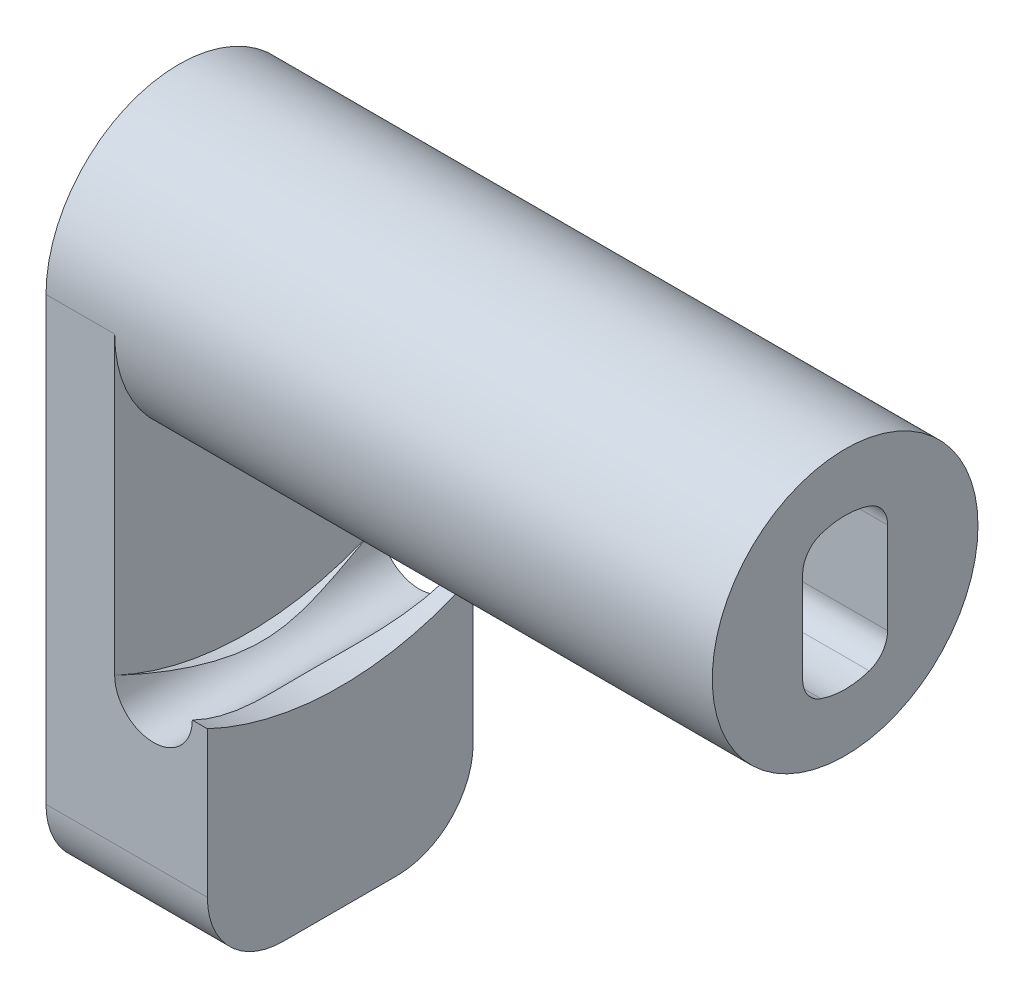
SolidWorks part; units mm, degrees
material "ABS"
ref_plane "Front Plane" through (0, 0, 0) normal (1, 0, 0) x (0, 1, 0)
ref_plane "Top Plane" through (0, 0, 0) normal (0, 0, 1) x (0, 1, 0)
ref_plane "Right Plane" through (0, 0, 0) normal (0, 1, 0) x (-1, 0, 0)
sketch "Sketch1" plane through (0, 0, 0) normal (1, 0, 0) x (0, 1, 0)
  circle A2 centre (0, 0) radius 8.7376
  dimension "D3" = 17.4752
extrude "Boss-Extrude1" add sketch "Sketch1" along normal blind 43.815
sketch "Sketch10" plane through (0, 0, 0) normal (-1, 0, 0) x (0, -1, 0)
  line L0 (0, 8.7376) -> (34.036, 8.7376)
  line L2 (34.036, 8.7376) -> (34.036, -8.7376)
  line L3 (34.036, -8.7376) -> (0, -8.7376)
  circle A0 centre (0, 0) radius 8.7376 construction
  arc A2 (0, 8.7376) -> (0, -8.7376) centre (0, 0) cw
  dimension "D1" = 34.036
extrude "Boss-Extrude3" add sketch "Sketch10" against normal blind 4.516 contours L0 A2 L3 L2
fillet "Fillet2" radius 5 2 edges at (2.258, -34.036, 8.7376) (2.258, -34.036, -8.7376)
sketch "Sketch14" [suppressed] plane through (0, 0, 0) normal (-1, 0, 0) x (0, 0, 1)
  line L0 (0.5115, -3.4237) -> (0.3944, -4.0089)
  line L1 (0, 0) -> (0, -4.064) construction
  line L2 (0, 0) -> (0.5606, -3.4335) construction
  line L3 (0.6039, -3.4087) -> (0.9011, -3.9262)
  line L4 (-0.6903, -3.3922) -> (-1.0005, -3.9021)
  line L5 (-0.5983, -3.4096) -> (-0.4961, -3.9976)
  line L6 (-1.8089, -2.9515) -> (-2.2748, -3.3245)
  line L7 (-1.7284, -2.9994) -> (-1.8334, -3.5869)
  line L8 (-2.7093, -2.1549) -> (-3.2746, -2.346)
  line L9 (-2.65, -2.2273) -> (-2.9496, -2.7435)
  line L10 (-3.2829, -1.0983) -> (-3.8795, -1.0846)
  line L11 (-3.252, -1.1867) -> (-3.7101, -1.5692)
  line L12 (-3.4605, 0.0907) -> (-4.0165, 0.3077)
  line L13 (-3.4617, -0.0029) -> (-4.023, -0.2057)
  line L14 (-3.2208, 1.2689) -> (-3.669, 1.6629)
  line L15 (-3.2539, 1.1813) -> (-3.8507, 1.1827)
  line L16 (-2.5926, 2.2939) -> (-2.879, 2.8175)
  line L17 (-2.6537, 2.223) -> (-3.214, 2.4284)
  line L18 (-1.6517, 3.0423) -> (-1.7417, 3.6323)
  line L19 (-1.7333, 2.9965) -> (-2.1896, 3.3812)
  line L20 (-0.5115, 3.4237) -> (-0.3944, 4.0089)
  line L21 (-0.6039, 3.4087) -> (-0.9011, 3.9262)
  line L22 (0.6903, 3.3922) -> (1.0005, 3.9021)
  line L23 (0.5983, 3.4096) -> (0.4961, 3.9976)
  line L24 (1.8089, 2.9515) -> (2.2748, 3.3245)
  line L25 (1.7284, 2.9994) -> (1.8334, 3.5869)
  line L26 (2.7093, 2.1549) -> (3.2746, 2.346)
  line L27 (2.65, 2.2273) -> (2.9496, 2.7435)
  line L28 (3.2829, 1.0983) -> (3.8795, 1.0846)
  line L29 (3.252, 1.1867) -> (3.7101, 1.5692)
  line L30 (3.4605, -0.0907) -> (4.0165, -0.3077)
  line L31 (3.4617, 0.0029) -> (4.023, 0.2057)
  line L32 (3.2208, -1.2689) -> (3.669, -1.6629)
  line L33 (3.2539, -1.1813) -> (3.8507, -1.1827)
  line L34 (2.5926, -2.2939) -> (2.879, -2.8175)
  line L35 (2.6537, -2.223) -> (3.214, -2.4284)
  line L36 (1.6517, -3.0423) -> (1.7417, -3.6323)
  line L37 (1.7333, -2.9965) -> (2.1896, -3.3812)
  line L38 (-0.1032, -4.0627) -> (0, -4.064)
  line L39 (-1.4865, -3.7824) -> (-1.39, -3.8189)
  line L40 (-2.6905, -3.0459) -> (-2.6123, -3.1132)
  line L41 (-3.5195, -2.032) -> (-3.57, -1.942)
  line L42 (-4.0023, -0.7057) -> (-4.0189, -0.6039)
  line L43 (-4.0023, 0.7057) -> (-3.9831, 0.8071)
  line L44 (-3.5195, 2.032) -> (-3.4668, 2.1207)
  line L45 (-2.6123, 3.1132) -> (-2.5324, 3.1785)
  line L46 (-1.39, 3.8189) -> (-1.2926, 3.853)
  line L47 (0, 4.064) -> (0.1032, 4.0627)
  line L48 (1.39, 3.8189) -> (1.4865, 3.7824)
  line L49 (2.6123, 3.1132) -> (2.6905, 3.0459)
  line L50 (3.5195, 2.032) -> (3.57, 1.942)
  line L51 (4.0023, 0.7057) -> (4.0189, 0.6039)
  line L52 (4.0023, -0.7057) -> (3.9831, -0.8071)
  line L53 (3.5195, -2.032) -> (3.4668, -2.1207)
  line L54 (2.6123, -3.1132) -> (2.5324, -3.1785)
  line L55 (1.39, -3.8189) -> (1.2926, -3.853)
  arc A0 (0.3497, -4.0489) -> (0, -4.064) centre (0, 0) cw
  arc A1 (0.3497, -4.0489) -> (0.3944, -4.0089) centre (0.3454, -3.9991) ccw
  arc A2 (0.5115, -3.4237) -> (0.6039, -3.4087) centre (0.5606, -3.4335) cw
  arc A3 (0.4203, -4.0631) -> (0.3944, -4.0089) centre (0.4434, -4.0187) cw
  arc A4 (0.4203, -4.0631) -> (0.7372, -4.2116) centre (2.3016, -0.4608) ccw
  arc A6 (0.9562, -3.9499) -> (0.9011, -3.9262) centre (0.9445, -3.9013) cw
  arc A7 (0.9562, -3.9499) -> (1.2926, -3.853) centre (0, 0) ccw
  arc A8 (-1.0562, -3.9243) -> (-1.39, -3.8189) centre (0, 0) cw
  arc A9 (-1.0562, -3.9243) -> (-1.0005, -3.9021) centre (-1.0432, -3.8761) ccw
  arc A10 (-0.6903, -3.3922) -> (-0.5983, -3.4096) centre (-0.6476, -3.4182) cw
  arc A11 (-0.4524, -4.0387) -> (-0.4961, -3.9976) centre (-0.4468, -3.9891) cw
  arc A12 (-0.4524, -4.0387) -> (-0.1032, -4.0627) centre (0, 0) ccw
  arc A13 (-2.3347, -3.3264) -> (-2.6123, -3.1132) centre (0, 0) cw
  arc A14 (-2.3347, -3.3264) -> (-2.2748, -3.3245) centre (-2.306, -3.2855) ccw
  arc A15 (-1.8089, -2.9515) -> (-1.7284, -2.9994) centre (-1.7776, -2.9906) cw
  arc A16 (-1.8064, -3.6405) -> (-1.8334, -3.5869) centre (-1.7842, -3.5957) cw
  arc A17 (-1.8064, -3.6405) -> (-1.4865, -3.7824) centre (0, 0) ccw
  arc A18 (-3.3316, -2.3273) -> (-3.5195, -2.032) centre (0, 0) cw
  arc A19 (-3.3316, -2.3273) -> (-3.2746, -2.346) centre (-3.2906, -2.2987) ccw
  arc A20 (-2.7093, -2.1549) -> (-2.65, -2.2273) centre (-2.6933, -2.2022) cw
  arc A21 (-2.9426, -2.8031) -> (-2.9496, -2.7435) centre (-2.9064, -2.7686) cw
  arc A22 (-2.9426, -2.8031) -> (-2.6905, -3.0459) centre (0, 0) ccw
  arc A23 (-3.9267, -1.0475) -> (-4.0023, -0.7057) centre (0, 0) cw
  arc A24 (-3.9267, -1.0475) -> (-3.8795, -1.0846) centre (-3.8784, -1.0346) ccw
  arc A25 (-3.2829, -1.0983) -> (-3.252, -1.1867) centre (-3.284, -1.1483) cw
  arc A26 (-3.7238, -1.6276) -> (-3.7101, -1.5692) centre (-3.678, -1.6076) cw
  arc A27 (-3.7238, -1.6276) -> (-3.57, -1.942) centre (0, 0) ccw
  arc A28 (-4.0481, 0.3587) -> (-4.0023, 0.7057) centre (0, 0) cw
  arc A29 (-4.0481, 0.3587) -> (-4.0165, 0.3077) centre (-3.9983, 0.3543) ccw
  arc A30 (-3.4605, 0.0907) -> (-3.4617, -0.0029) centre (-3.4787, 0.0442) cw
  arc A31 (-4.0559, -0.2558) -> (-4.023, -0.2057) centre (-4.006, -0.2527) cw
  arc A32 (-4.0559, -0.2558) -> (-4.0189, -0.6039) centre (0, 0) ccw
  arc A33 (-3.6813, 1.7216) -> (-3.5195, 2.032) centre (0, 0) cw
  arc A34 (-3.6813, 1.7216) -> (-3.669, 1.6629) centre (-3.636, 1.7005) ccw
  arc A35 (-3.2208, 1.2689) -> (-3.2539, 1.1813) centre (-3.2538, 1.2313) cw
  arc A36 (-3.8988, 1.1468) -> (-3.8507, 1.1827) centre (-3.8509, 1.1327) cw
  arc A37 (-3.8988, 1.1468) -> (-3.9831, 0.8071) centre (0, 0) ccw
  arc A38 (-2.8705, 2.8769) -> (-2.6123, 3.1132) centre (0, 0) cw
  arc A39 (-2.8705, 2.8769) -> (-2.879, 2.8175) centre (-2.8352, 2.8415) ccw
  arc A40 (-2.5926, 2.2939) -> (-2.6537, 2.223) centre (-2.6365, 2.2699) cw
  arc A41 (-3.2715, 2.4111) -> (-3.214, 2.4284) centre (-3.2312, 2.3815) cw
  arc A42 (-3.2715, 2.4111) -> (-3.4668, 2.1207) centre (0, 0) ccw
  arc A43 (-1.7134, 3.6852) -> (-1.39, 3.8189) centre (0, 0) cw
  arc A44 (-1.7134, 3.6852) -> (-1.7417, 3.6323) centre (-1.6923, 3.6398) ccw
  arc A45 (-1.6517, 3.0423) -> (-1.7333, 2.9965) centre (-1.7011, 3.0348) cw
  arc A46 (-2.2495, 3.3846) -> (-2.1896, 3.3812) centre (-2.2218, 3.343) cw
  arc A47 (-2.2495, 3.3846) -> (-2.5324, 3.1785) centre (0, 0) ccw
  arc A48 (-0.3497, 4.0489) -> (0, 4.064) centre (0, 0) cw
  arc A49 (-0.3497, 4.0489) -> (-0.3944, 4.0089) centre (-0.3454, 3.9991) ccw
  arc A50 (-0.5115, 3.4237) -> (-0.6039, 3.4087) centre (-0.5606, 3.4335) cw
  arc A51 (-0.9562, 3.9499) -> (-0.9011, 3.9262) centre (-0.9445, 3.9013) cw
  arc A52 (-0.9562, 3.9499) -> (-1.2926, 3.853) centre (0, 0) ccw
  arc A53 (1.0562, 3.9243) -> (1.39, 3.8189) centre (0, 0) cw
  arc A54 (1.0562, 3.9243) -> (1.0005, 3.9021) centre (1.0432, 3.8761) ccw
  arc A55 (0.6903, 3.3922) -> (0.5983, 3.4096) centre (0.6476, 3.4182) cw
  arc A56 (0.4524, 4.0387) -> (0.4961, 3.9976) centre (0.4468, 3.9891) cw
  arc A57 (0.4524, 4.0387) -> (0.1032, 4.0627) centre (0, 0) ccw
  arc A58 (2.3347, 3.3264) -> (2.6123, 3.1132) centre (0, 0) cw
  arc A59 (2.3347, 3.3264) -> (2.2748, 3.3245) centre (2.306, 3.2855) ccw
  arc A60 (1.8089, 2.9515) -> (1.7284, 2.9994) centre (1.7776, 2.9906) cw
  arc A61 (1.8064, 3.6405) -> (1.8334, 3.5869) centre (1.7842, 3.5957) cw
  arc A62 (1.8064, 3.6405) -> (1.4865, 3.7824) centre (0, 0) ccw
  arc A63 (3.3316, 2.3273) -> (3.5195, 2.032) centre (0, 0) cw
  arc A64 (3.3316, 2.3273) -> (3.2746, 2.346) centre (3.2906, 2.2987) ccw
  arc A65 (2.7093, 2.1549) -> (2.65, 2.2273) centre (2.6933, 2.2022) cw
  arc A66 (2.9426, 2.8031) -> (2.9496, 2.7435) centre (2.9064, 2.7686) cw
  arc A67 (2.9426, 2.8031) -> (2.6905, 3.0459) centre (0, 0) ccw
  arc A68 (3.9267, 1.0475) -> (4.0023, 0.7057) centre (0, 0) cw
  arc A69 (3.9267, 1.0475) -> (3.8795, 1.0846) centre (3.8784, 1.0346) ccw
  arc A70 (3.2829, 1.0983) -> (3.252, 1.1867) centre (3.284, 1.1483) cw
  arc A71 (3.7238, 1.6276) -> (3.7101, 1.5692) centre (3.678, 1.6076) cw
  arc A72 (3.7238, 1.6276) -> (3.57, 1.942) centre (0, 0) ccw
  arc A73 (4.0481, -0.3587) -> (4.0023, -0.7057) centre (0, 0) cw
  arc A74 (4.0481, -0.3587) -> (4.0165, -0.3077) centre (3.9983, -0.3543) ccw
  arc A75 (3.4605, -0.0907) -> (3.4617, 0.0029) centre (3.4787, -0.0442) cw
  arc A76 (4.0559, 0.2558) -> (4.023, 0.2057) centre (4.006, 0.2527) cw
  arc A77 (4.0559, 0.2558) -> (4.0189, 0.6039) centre (0, 0) ccw
  arc A78 (3.6813, -1.7216) -> (3.5195, -2.032) centre (0, 0) cw
  arc A79 (3.6813, -1.7216) -> (3.669, -1.6629) centre (3.636, -1.7005) ccw
  arc A80 (3.2208, -1.2689) -> (3.2539, -1.1813) centre (3.2538, -1.2313) cw
  arc A81 (3.8988, -1.1468) -> (3.8507, -1.1827) centre (3.8509, -1.1327) cw
  arc A82 (3.8988, -1.1468) -> (3.9831, -0.8071) centre (0, 0) ccw
  arc A83 (2.8705, -2.8769) -> (2.6123, -3.1132) centre (0, 0) cw
  arc A84 (2.8705, -2.8769) -> (2.879, -2.8175) centre (2.8352, -2.8415) ccw
  arc A85 (2.5926, -2.2939) -> (2.6537, -2.223) centre (2.6365, -2.2699) cw
  arc A86 (3.2715, -2.4111) -> (3.214, -2.4284) centre (3.2312, -2.3815) cw
  arc A87 (3.2715, -2.4111) -> (3.4668, -2.1207) centre (0, 0) ccw
  arc A88 (1.7134, -3.6852) -> (1.39, -3.8189) centre (0, 0) cw
  arc A89 (1.7134, -3.6852) -> (1.7417, -3.6323) centre (1.6923, -3.6398) ccw
  arc A90 (1.6517, -3.0423) -> (1.7333, -2.9965) centre (1.7011, -3.0348) cw
  arc A91 (2.2495, -3.3846) -> (2.1896, -3.3812) centre (2.2218, -3.343) cw
  arc A92 (2.2495, -3.3846) -> (2.5324, -3.1785) centre (0, 0) ccw
  point P207 (0, 0)
  dimension "D1" = 4.064
  dimension "D2" = 0.05
  dimension "D3" = 0.05
  dimension "D4" = 0.04
  dimension "D5" = 18
  dimension "D6" = 0.5968
  dimension "D8" = 0.35
sketch "Sketch15" plane through (4.516, 0, 0) normal (1, 0, 0) x (0, 1, 0)
  line L1 (-29.036, 8.7376) -> (-18.796, 8.7376)
  line L2 (-18.796, 8.7376) -> (-18.796, -8.7376)
  line L3 (0, 8.7376) -> (-29.036, 8.7376) construction
  line L4 (-29.036, -8.7376) -> (-18.796, -8.7376)
  line L5 (-34.036, 3.7376) -> (-34.036, -3.7376) construction
  line L6 (-34.036, 3.7376) -> (-34.036, -3.7376)
  line L8 (-29.036, -8.7376) -> (0, -8.7376) construction
  line L13 (0, 8.7376) -> (-29.036, 8.7376)
  line L14 (-34.036, 3.7376) -> (-34.036, -3.7376)
  line L15 (-29.036, -8.7376) -> (0, -8.7376)
  line L17 (-34.036, 3.7376) -> (-34.036, -3.7376)
  arc A0 (-29.036, 8.7376) -> (-34.036, 3.7376) centre (-29.036, 3.7376) ccw construction
  arc A1 (-34.036, -3.7376) -> (-29.036, -8.7376) centre (-29.036, -3.7376) ccw construction
  arc A2 (-29.036, 8.7376) -> (-34.036, 3.7376) centre (-29.036, 3.7376) ccw
  arc A3 (-34.036, -3.7376) -> (-29.036, -8.7376) centre (-29.036, -3.7376) ccw
  arc A7 (-29.036, 8.7376) -> (-34.036, 3.7376) centre (-29.036, 3.7376) ccw
  arc A8 (-34.036, -3.7376) -> (-29.036, -8.7376) centre (-29.036, -3.7376) ccw
  arc A9 (0, 8.7376) -> (0, -8.7376) centre (0, 0) ccw
  arc A10 (-29.036, 8.7376) -> (-34.036, 3.7376) centre (-29.036, 3.7376) ccw
  arc A11 (-34.036, -3.7376) -> (-29.036, -8.7376) centre (-29.036, -3.7376) ccw
  arc A12 (0, 8.7376) -> (0, -8.7376) centre (0, 0) ccw
  dimension "D1" = 15.24
  dimension "D2" = 0
extrude "Boss-Extrude4" add sketch "Sketch15" along normal blind 6.096
sketch "Sketch21" plane through (10.612, 0, 0) normal (1, 0, 0) x (0, 1, 0)
  line L2 (-18.796, -8.7376) -> (-18.796, 8.7376)
  line L4 (-29.036, 8.7376) -> (-18.796, 8.7376) construction
  line L5 (-19.431, -8.7376) -> (-18.796, -8.7376)
  line L6 (-18.796, 8.7376) -> (-18.796, -8.7376) construction
  line L8 (-18.796, -8.7376) -> (0, -8.7376) construction
  line L14 (-18.796, -8.7376) -> (-18.796, 8.7376) construction
  line L20 (-18.796, 8.7376) -> (-29.036, 8.7376)
  arc A2 (-19.431, -8.7376) -> (-19.431, 8.7376) centre (-1.0855, 0) cw
  dimension "D4" = 20.32
  dimension "D2" = 0.635
  dimension "D3" = 0.635
extrude "Cut-Extrude8" cut sketch "Sketch21" against normal up to surface (6.096 mm away)
sketch "Sketch22" plane through (43.815, 0, 0) normal (1, 0, 0) x (0, 1, 0)
  line L7 (-4.0897, -2.794) -> (4.0897, 2.794) construction
  line L8 (-4.0897, 2.794) -> (4.0897, -2.794) construction
  line L11 (-4.0897, -2.794) -> (4.0897, -2.794)
  line L13 (-4.0897, 2.794) -> (4.0897, 2.794)
  line L15 (-4.0897, -2.794) -> (4.0897, 2.794) construction
  line L16 (-4.0897, 2.794) -> (4.0897, -2.794) construction
  arc A3 (-4.0897, 2.794) -> (-4.0897, -2.794) centre (0, 0) ccw
  arc A4 (4.0897, -2.794) -> (4.0897, 2.794) centre (0, 0) ccw
  dimension "D2" = 9.906
  dimension "D3" = 5.588
extrude "Cut-Extrude10" cut sketch "Sketch22" against normal blind 12.192
fillet "Fillet11" radius 1.778 4 edges at (37.719, 4.0897, -2.794) (37.719, 4.0897, 2.794) (37.719, -4.0897, -2.794) (37.719, -4.0897, 2.794)
sketch "Sketch25" plane through (0, 0, -8.7376) normal (0, 0, -1) x (1, 0, 0)
  line L3 (4.516, 19.431) -> (4.516, 0) construction
  line L4 (4.516, 19.431) -> (10.612, 19.431) construction
  circle A0 centre (7.0687, 19.431) radius 2.5527
  dimension "D1" = 5.1054
extrude "Cut-Extrude14" cut sketch "Sketch25" against normal through all
sketch "Sketch26" plane through (0, 0, 0) normal (-1, 0, 0) x (0, -1, 0)
  line L1 (3.6846, 1.7145) -> (7.1771, 1.7145)
  line L2 (3.6846, 1.7145) -> (3.6846, -1.7145) construction
  line L3 (3.6846, -1.7145) -> (7.1771, -1.7145)
  line L4 (7.1771, 1.7145) -> (7.1771, -1.7145)
  arc A0 (3.6846, 1.7145) -> (3.6846, -1.7145) centre (0, 0) ccw
  dimension "D1" = 8.128
  dimension "D2" = 3.429
  dimension "D3" = 3.4925
extrude "Cut-Extrude15" cut sketch "Sketch26" against normal blind 21.59
fillet "Fillet12" radius 1.5875 4 edges at (10.795, -3.6846, 1.7145) (10.795, -7.1771, 1.7145) (10.795, -3.6846, -1.7145) (10.795, -7.1771, -1.7145)
